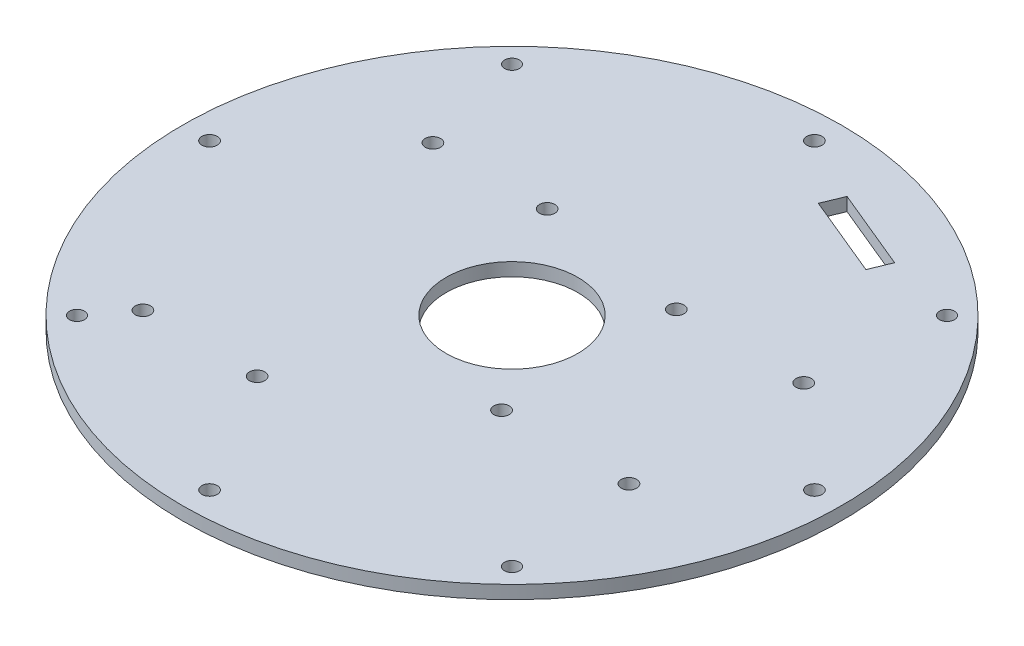
SolidWorks part; units mm, degrees
ref_plane "Front Plane" through (0, 0, 0) normal (0, 0, 1) x (1, 0, 0)
ref_plane "Top Plane" through (0, 0, 0) normal (0, 1, 0) x (1, 0, 0)
ref_plane "Right Plane" through (0, 0, 0) normal (1, 0, 0) x (0, 0, -1)
sketch "Sketch1" plane through (0, 0, 0) normal (0, 1, 0) x (1, 0, 0)
  line L0 (-49.4975, -49.4975) -> (49.4975, 49.4975) construction
  line L1 (49.4975, -49.4975) -> (-49.4975, 49.4975) construction
  line L2 (0, 0) -> (130.1462, 0) construction
  circle A1 centre (0, 0) radius 75
  circle A6 centre (0, 0) radius 70 construction
  circle A7 centre (49.4975, 49.4975) radius 1.7
  circle A8 centre (-49.4975, 49.4975) radius 1.7
  circle A9 centre (-49.4975, -49.4975) radius 1.7
  circle A10 centre (49.4975, -49.4975) radius 1.7
  circle A11 centre (0, 0) radius 15
  point P15 (0, 0)
  point P19 (0, 0)
  dimension "D3" = 150
  dimension "D4" = 140
  dimension "D6" = 3.4
  dimension "D7" = 30
  dimension "D5" = 45
extrude "Boss-Extrude1" add sketch "Sketch1" along normal blind 3
sketch "Sketch2" plane through (0, 0, 0) normal (0, 1, 0) x (1, 0, 0)
  circle A0 centre (0, 0) radius 68.825 construction
  circle A1 centre (0, 68.825) radius 1.75
  circle A2 centre (68.825, 0) radius 1.75
  circle A3 centre (0, -68.825) radius 1.75
  circle A4 centre (-68.825, 0) radius 1.75
  dimension "D1" = 137.65
  dimension "D2" = 3.5
extrude "Cut-Extrude2" cut sketch "Sketch2" along normal through all
sketch "Sketch3" plane through (0, 0, 0) normal (0, 1, 0) x (1, 0, 0)
  line L0 (-30, 0) -> (32, 0) construction
  line L9 (-43, -41) -> (-17, -41) construction
  line L10 (-43, -41) -> (-43, 25) construction
  line L11 (-43, 25) -> (-17, 25) construction
  line L12 (-17, -41) -> (-17, 25) construction
  line L13 (-43, -41) -> (-17, 25) construction
  line L14 (-43, 25) -> (-17, -41) construction
  line L15 (46.4944, -19.8841) -> (17.5056, -19.8841) construction
  line L16 (46.4944, -19.8841) -> (46.4944, 19.8841) construction
  line L17 (46.4944, 19.8841) -> (17.5056, 19.8841) construction
  line L18 (17.5056, -19.8841) -> (17.5056, 19.8841) construction
  line L19 (46.4944, -19.8841) -> (17.5056, 19.8841) construction
  line L20 (46.4944, 19.8841) -> (17.5056, -19.8841) construction
  line L21 (31.2431, 49.2962) -> (12.7655, 56.9499)
  line L22 (-45, 27) -> (-15, 27) construction
  line L23 (-45, 27) -> (-45, -43) construction
  line L24 (-45, -43) -> (-15, -43) construction
  line L25 (-15, 27) -> (-15, -43) construction
  line L30 (31.2431, 49.2962) -> (33.1565, 53.9156)
  line L31 (12.7655, 56.9499) -> (14.6789, 61.5693)
  line L32 (33.1565, 53.9156) -> (14.6789, 61.5693)
  line L33 (31.2431, 49.2962) -> (14.6789, 61.5693) construction
  line L34 (12.7655, 56.9499) -> (33.1565, 53.9156) construction
  line L35 (0, 0) -> (22.961, 55.4328) construction
  circle A0 centre (-43, 25) radius 1.75
  circle A1 centre (-17, 25) radius 1.75
  circle A2 centre (-17, -41) radius 1.75
  circle A3 centre (-43, -41) radius 1.75
  circle A4 centre (17.5056, 19.8841) radius 1.75
  circle A5 centre (46.4944, -19.8841) radius 1.75
  circle A6 centre (46.4944, 19.8841) radius 1.75
  circle A7 centre (17.5056, -19.8841) radius 1.75
  circle A8 centre (0, 0) radius 63.5 construction
  point P0 (-30, -8)
  point P5 (32, 0)
  point P28 (22.961, 55.4328)
  dimension "D5" = 3.5
  dimension "D9" = 127
  dimension "D1" = 30
  dimension "D2" = 32
  dimension "D3" = 26
  dimension "D4" = 66
  dimension "D6" = 49.2125
  dimension "D7" = 53.91
  dimension "D8" = 8
  dimension "D10" = 2
  dimension "D11" = 2
  dimension "D12" = 2
  dimension "D13" = 2
  dimension "D14" = 5
  dimension "D15" = 20
  dimension "D16" = 67.5
  dimension "D17" = 60
extrude "Cut-Extrude3" cut sketch "Sketch3" along normal through all
